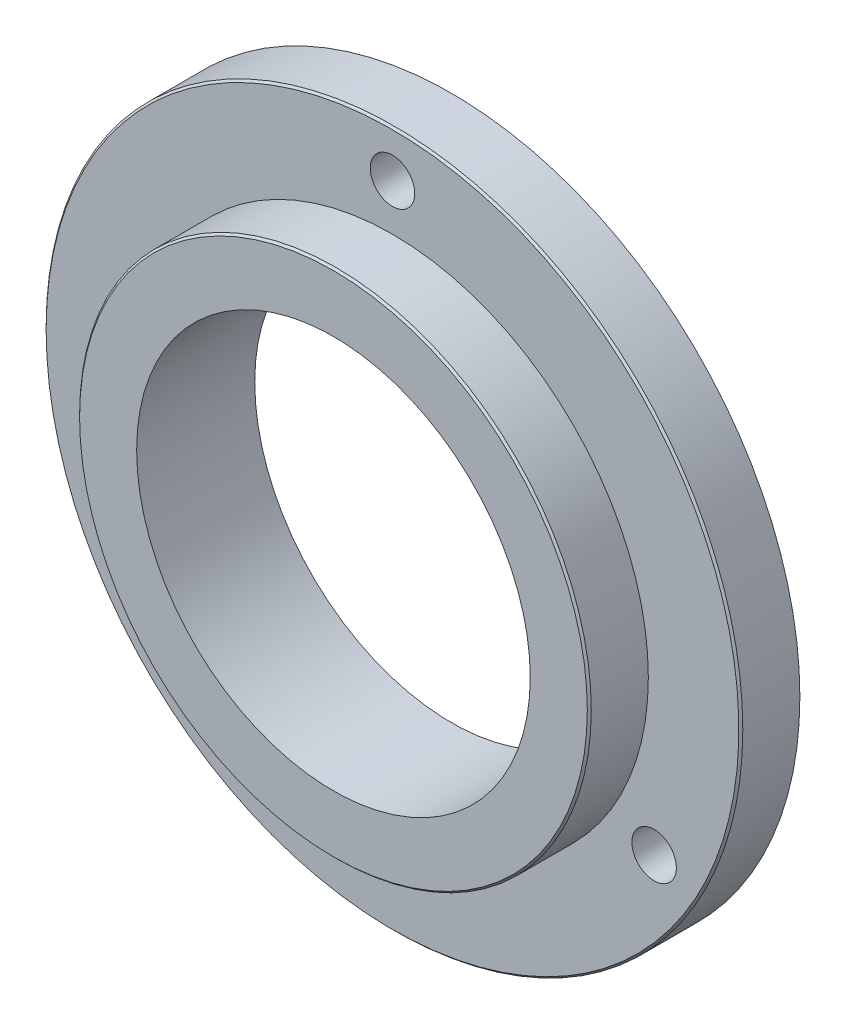
SolidWorks part; units mm, degrees
ref_plane "Plan de face" through (0, 0, 0) normal (0, 0, 1) x (1, 0, 0)
ref_plane "Plan de dessus" through (0, 0, 0) normal (0, 1, 0) x (1, 0, 0)
ref_plane "Plan de droite" through (0, 0, 0) normal (1, 0, 0) x (0, 0, -1)
sketch "Esquisse1" [suppressed] plane through (0, 0, 0) normal (0, 0, 1) x (1, 0, 0)
  circle A0 centre (0, 0) radius 40.8746
sketch "Esquisse10" plane through (0, 0, 0) normal (0, 0, 1) x (1, 0, 0)
  circle A0 centre (0, 0) radius 13
  circle A1 centre (0, 0) radius 10
extrude "Boss.-Extru.2" add sketch "Esquisse10" along normal blind 3
sketch "Esquisse11" plane through (0, 0, 0) normal (0, 0, -1) x (-1, 0, 0)
  circle A0 centre (0, 0) radius 10
  circle A1 centre (0, 0) radius 17.7
extrude "Boss.-Extru.3" add sketch "Esquisse11" along normal blind 3
sketch "Sketch4" plane through (0, 0, 0) normal (0, 0, 1) x (1, 0, 0)
  line L0 (0, 17.7) -> (0, 13)
  circle A0 centre (0, 0) radius 17.7 construction
  circle A1 centre (0, 0) radius 13 construction
hole_wizard "#4-40 Tapped Hole1" positions "Sketch5" profile "Sketch6" tap size "#4-40" standard "ANSI Inch" end condition through all
sketch "Sketch5" plane through (0, 0, 0) normal (0, 0, 1) x (1, 0, 0)
  line L0 (0, 17.7) -> (0, 13) construction
  point P0 (0, 15.35)
sketch "Sketch6" plane through (0, 15.35, 0) normal (1, 0, 0) x (0, -1, 0)
  line L0 (0, 0) -> (0, 3)
  line L1 (0, 3) -> (1.1303, 3)
  line L2 (1.1303, 3) -> (1.1303, 0)
  line L5 (1.1303, 0) -> (0, 0)
  line L11 (0, -6.35) -> (0, 107.95) construction
  dimension "Thru Tap Drill Dia." = 2.2606
  dimension "Thru Tap Drill Depth" = 3
pattern_circular "CirPattern1" count 3 over 360 about axis through (0, 0, 0) along (0, 0, 1) of "#4-40 Tapped Hole1"
chamfer "Chamfer1" distance 0.1 angle 45 1 edges at (-17.7, 0, 0)
chamfer "Chamfer2" distance 0.1 angle 45 1 edges at (13, 0, 3)
